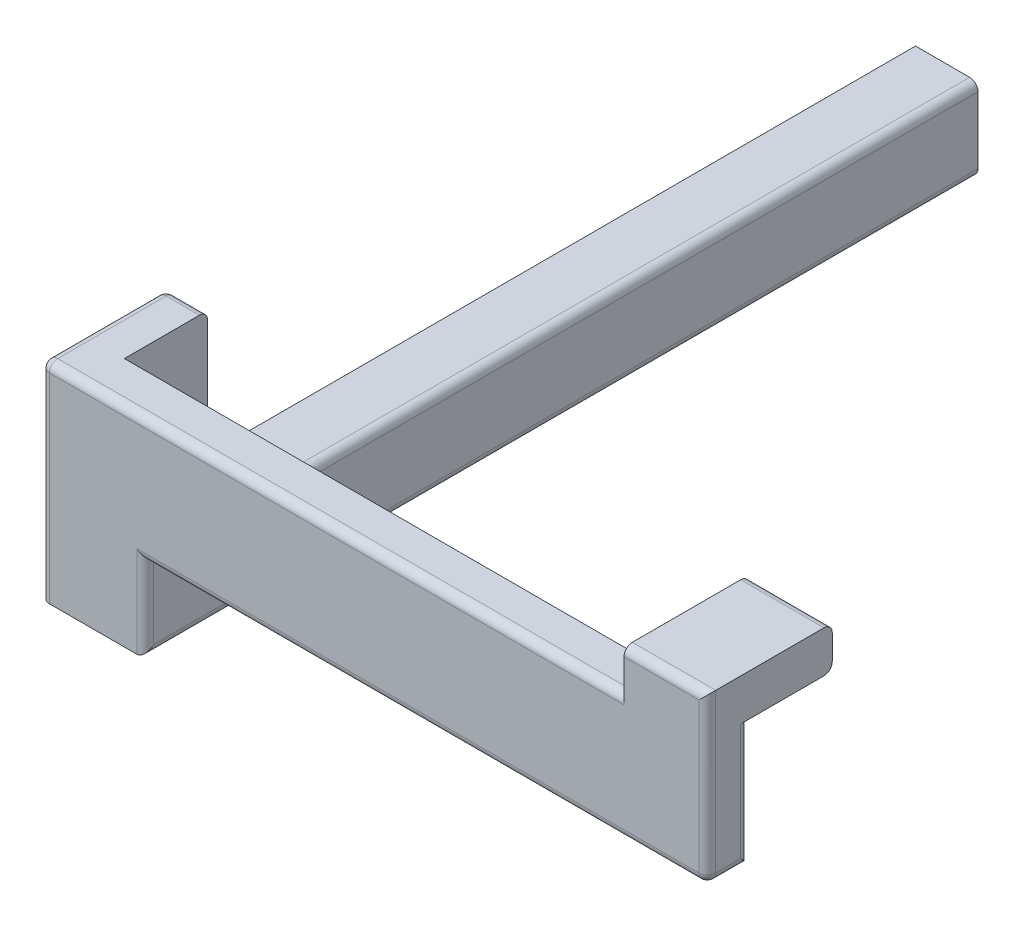
SolidWorks part; units mm, degrees
ref_plane "Front Plane" through (0, 0, 0) normal (1, 0, 0) x (0, 1, 0)
ref_plane "Top Plane" through (0, 0, 0) normal (0, 0, 1) x (0, 1, 0)
ref_plane "Right Plane" through (0, 0, 0) normal (0, 1, 0) x (-1, 0, 0)
sketch "long-leg" plane through (0, 0, 0) normal (0, 0, 1) x (0, 1, 0)
  line L1 (-17.5141, 6.3898) -> (12.4859, 6.3898)
  line L2 (-17.5141, 6.3898) -> (-17.5141, -143.6102)
  line L3 (-17.5141, -143.6102) -> (12.4859, -143.6102)
  line L4 (12.4859, 6.3898) -> (12.4859, -143.6102)
  dimension "D1" = 150
  dimension "D2" = 30
extrude "long_leg_extrude" add sketch "long-leg" along normal blind 10
sketch "Sketch2" plane through (-6.3898, 0, 0) normal (-1, 0, 0) x (0, -1, 0)
  line L0 (17.5141, 10) -> (17.5141, 0) construction
  line L1 (-12.4859, 10) -> (17.5141, 10)
  line L2 (-12.4859, 10) -> (-12.4859, -20)
  line L3 (-12.4859, -20) -> (17.5141, -20)
  line L4 (17.5141, 10) -> (17.5141, -20)
  line L5 (-12.4859, 0) -> (17.5141, 0) construction
  dimension "D1" = 0
  dimension "D2" = 20
extrude "Boss-Extrude2" add sketch "Sketch2" along normal blind 10
sketch "Sketch6" plane through (0, -17.5141, 0) normal (0, -1, 0) x (1, 0, 0)
  line L0 (-16.3898, 10) -> (143.6102, 10) construction
  line L1 (-6.3898, 10) -> (8.6102, 10)
  line L2 (-6.3898, 10) -> (-6.3898, -190)
  line L3 (-6.3898, -190) -> (8.6102, -190)
  line L4 (8.6102, 10) -> (8.6102, -190)
  line L5 (-16.3898, -20) -> (-16.3898, 10) construction
  line L7 (-16.3898, 10) -> (-6.3898, 10)
  line L8 (-16.3898, 10) -> (-16.3898, -20)
  line L9 (-16.3898, -20) -> (-6.3898, -20)
  line L10 (-6.3898, 10) -> (-6.3898, -20)
  line M5 (-6.3898, 0) -> (143.6102, 0)
  line M7 (143.6102, 10) -> (-16.3898, 10)
  line M8 (-16.3898, 10) -> (-16.3898, -20)
  line M9 (-16.3898, -20) -> (-6.3898, -20)
  line M10 (-6.3898, -20) -> (-6.3898, 0)
  dimension "D1" = 15
  dimension "D2" = 10
  dimension "D3" = 200
extrude "long leg down" add sketch "Sketch6" along normal blind 20 contours L2 M7 M8 M9 M10 | L4 L2 L3 M5 M10 | L4 L2 M7 M5
sketch "Sketch8" plane through (0, -37.5141, 0) normal (0, -1, 0) x (1, 0, 0)
  line L0 (8.6102, 10) -> (8.6102, -190) construction
  line L1 (-6.3898, -190) -> (28.6102, -190)
  line L2 (-6.3898, -190) -> (-6.3898, -170)
  line L3 (-6.3898, -170) -> (28.6102, -170)
  line L4 (28.6102, -190) -> (28.6102, -170)
  dimension "D1" = 20
  dimension "D2" = 20
sketch "Sketch9" plane through (0, 0, 0) normal (0, 0, -1) x (1, 0, 0)
  line L1 (143.6102, 17.5141) -> (-6.3898, 17.5141)
  line L2 (143.6102, 17.5141) -> (143.6102, -12.4859)
  line L3 (143.6102, -12.4859) -> (-6.3898, -12.4859)
  line L4 (-6.3898, 17.5141) -> (-6.3898, -12.4859)
  line L5 (-6.3898, -12.4859) -> (-6.3898, 17.5141) construction
  line L6 (143.6102, -12.4859) -> (-6.3898, -12.4859) construction
  dimension "D1" = 0
  dimension "D2" = 0
extrude "Boss-Extrude7" [suppressed] add sketch "Sketch9" along normal blind 10
sketch "Sketch11" plane through (0, 0, 10) normal (0, 0, 1) x (1, 0, 0)
  line L0 (-16.3898, -37.5141) -> (-16.3898, 12.4859) construction
  line L1 (143.6102, 12.4859) -> (-16.3898, 12.4859)
  line L2 (143.6102, 12.4859) -> (143.6102, -17.5141)
  line L3 (143.6102, -17.5141) -> (-16.3898, -17.5141)
  line L4 (-16.3898, 12.4859) -> (-16.3898, -17.5141)
  line L5 (8.6102, -17.5141) -> (143.6102, -17.5141) construction
  dimension "D1" = 0
  dimension "D2" = 0
sketch "Sketch12" plane through (0, 12.4859, 0) normal (0, 1, 0) x (-1, 0, 0)
  line L0 (-143.6102, 0) -> (6.3898, 0) construction
  line L1 (-143.6102, 10) -> (-123.6102, 10)
  line L2 (-143.6102, 10) -> (-143.6102, -20)
  line L3 (-143.6102, -20) -> (-123.6102, -20)
  line L4 (-123.6102, 10) -> (-123.6102, -20)
  dimension "D1" = 20
  dimension "D2" = 20
extrude "Boss-Extrude8" add sketch "Sketch12" along normal blind 10
sketch "Sketch13" plane through (-6.3898, 0, 0) normal (-1, 0, 0) x (0, -1, 0)
  line L0 (37.5141, -190) -> (17.5141, -190) construction
  line L1 (30.5591, -190) -> (24.5591, -190)
  line L2 (30.5591, -190) -> (30.5591, -185)
  line L3 (30.5591, -185) -> (24.5591, -185)
  line L4 (24.5591, -190) -> (24.5591, -185)
  line L5 (30.5591, -190) -> (24.5591, -185) construction
  line L6 (30.5591, -185) -> (24.5591, -190) construction
  line L8 (21.5591, -180) -> (33.5591, -180)
  line L9 (21.5591, -180) -> (21.5591, -185)
  line L10 (21.5591, -185) -> (33.5591, -185)
  line L11 (33.5591, -180) -> (33.5591, -185)
  line L12 (21.5591, -180) -> (33.5591, -185) construction
  line L13 (21.5591, -185) -> (33.5591, -180) construction
  point P0 (27.5591, -187.5)
  point P7 (27.5591, -182.5)
  point P12 (27.5591, -185)
  point P14 (29.728, -166.3044)
  line M9 (17.5141, -190) -> (37.5141, -190)
  dimension "D1" = 0
  dimension "D2" = 6
  dimension "D3" = 12
  dimension "D4" = 0
  dimension "D5" = 0
  dimension "D6" = 5
  dimension "D7" = 5
extrude "Cut-Extrude2" cut sketch "Sketch13" against normal blind 10 contours L11 L8 L9 L10 L3 | L4 L2 L3 M9
fillet "Fillet1" radius 2 6 edges at (133.6102, 12.4859, -20) (133.6102, 22.4859, -20) (133.6102, 22.4859, 10) (143.6102, 2.4859, 10) (-16.3898, -12.5141, 10) (-16.3898, -12.5141, -20)
fillet "Fillet2" radius 2 7 edges at (75.1102, -17.5141, 10) (143.0244, -17.5141, 9.4142) (143.6102, -17.5141, 4) (143.6102, -2.5141, 0) (8.6102, -37.5141, -90) (8.6102, -27.5141, 10) (-6.3898, -37.5141, -105)
fillet "Fillet3" radius 2 1 edges at (8.6102, -17.5141, -95)
fillet "Fillet4" radius 2 5 edges at (54.6102, 12.4859, 10) (-15.804, 12.4859, 9.4142) (-16.3898, 12.4859, -5) (-15.804, 12.4859, -19.4142) (-10.3898, 12.4859, -20)
